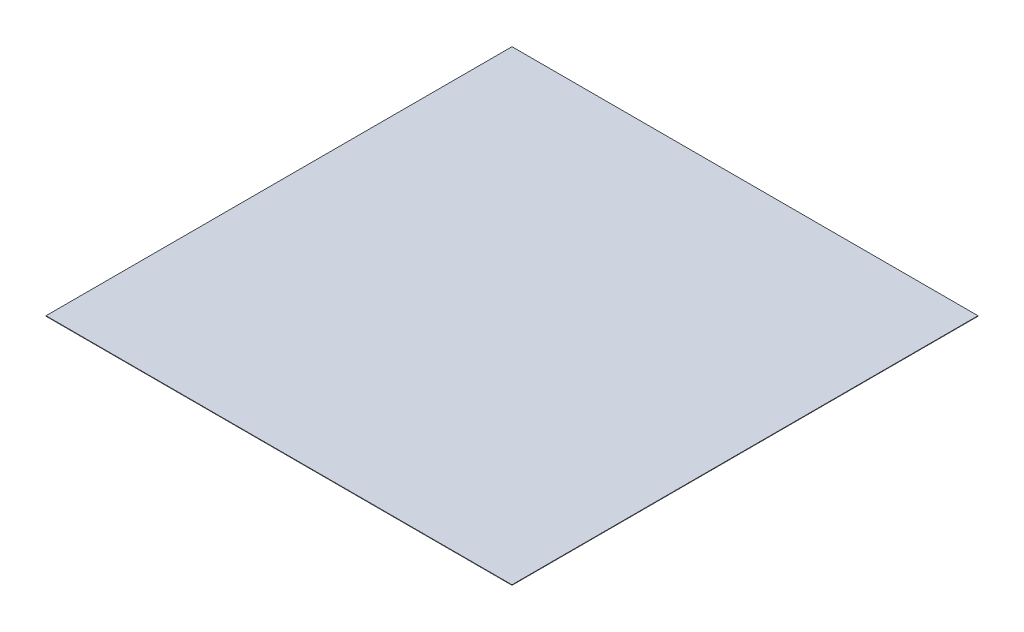
SolidWorks part; units mm, degrees
ref_plane "Front Plane" through (0, 0, 0) normal (0, 0, 1) x (1, 0, 0)
ref_plane "Top Plane" through (0, 0, 0) normal (0, 1, 0) x (1, 0, 0)
ref_plane "Right Plane" through (0, 0, 0) normal (1, 0, 0) x (0, 0, -1)
sketch "Sketch1" plane through (0, 0, 0) normal (0, 1, 0) x (1, 0, 0)
  line L1 (506.2341, 1270) -> (-2033.7659, 1270)
  line L2 (506.2341, 1270) -> (506.2341, -1270)
  line L3 (506.2341, -1270) -> (-2033.7659, -1270)
  line L4 (-2033.7659, 1270) -> (-2033.7659, -1270)
  line L5 (506.2341, 1270) -> (-2033.7659, -1270) construction
  line L6 (506.2341, -1270) -> (-2033.7659, 1270) construction
  point P0 (-763.7659, 0)
  dimension "D1" = 2540
  dimension "D2" = 2540
extrude "Boss-Extrude1" add sketch "Sketch1" along normal blind 2.54
